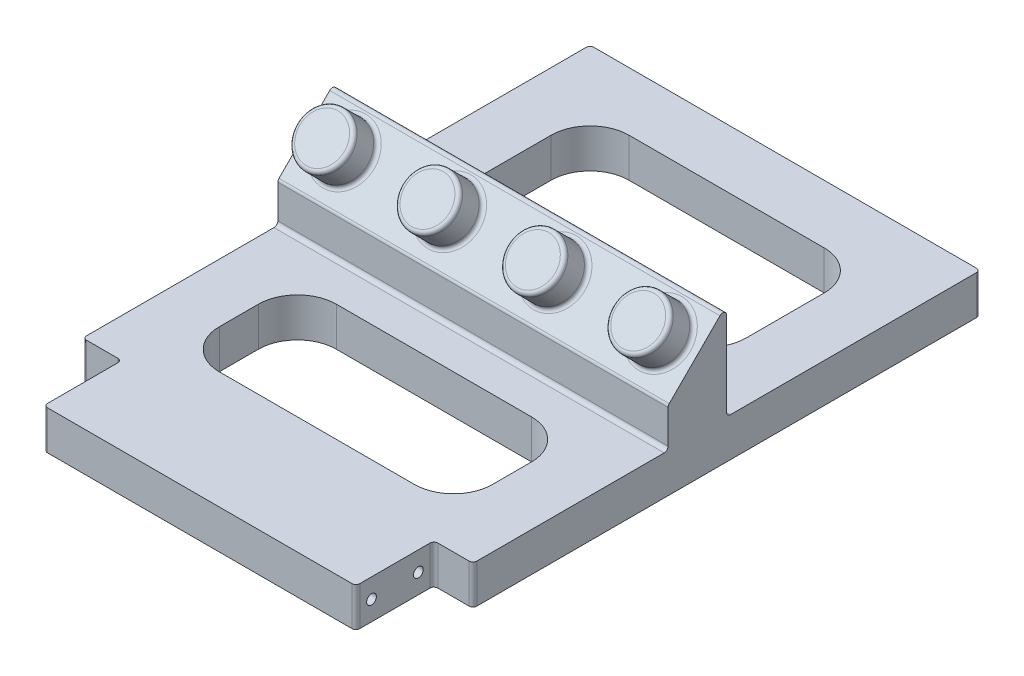
SolidWorks part; units mm, degrees
ref_plane "前视基准面" through (0, 0, 0) normal (0, 0, 1) x (1, 0, 0)
ref_plane "上视基准面" through (0, 0, 0) normal (0, 1, 0) x (1, 0, 0)
ref_plane "右视基准面" through (0, 0, 0) normal (1, 0, 0) x (0, 0, -1)
sketch "草图1" plane through (0, 0, 0) normal (0, 1, 0) x (1, 0, 0)
  line L1 (-50, -75) -> (50, -75)
  line L2 (-50, -75) -> (-50, 75)
  line L3 (-50, 75) -> (50, 75)
  line L4 (50, -75) -> (50, 75)
  line L5 (-50, -75) -> (50, 75) construction
  line L6 (-50, 75) -> (50, -75) construction
  point P0 (0, 0)
  dimension "D1" = 100
  dimension "D2" = 150
extrude "凸台-拉伸1" add sketch "草图1" along normal mid plane 10
sketch "草图6" plane through (50, 0, 0) normal (1, 0, 0) x (0, 0, -1)
  line L0 (-75, -5) -> (75, -5) construction
  line L1 (-55, -5) -> (-75, -5)
  line L2 (-55, -5) -> (-55, 5)
  line L3 (-55, 5) -> (-75, 5)
  line L4 (-75, -5) -> (-75, 5)
  line L5 (-55, -5) -> (-75, 5) construction
  line L6 (-55, 5) -> (-75, -5) construction
  point P0 (-65, 0)
  dimension "D1" = 20
extrude "切除-拉伸2" cut sketch "草图6" against normal blind 10
sketch "草图8" plane through (40, 0, 0) normal (1, 0, 0) x (0, 0, -1)
  line L0 (-55, -5) -> (-55, 5) construction
  line L1 (-55, -5) -> (-75, -5) construction
  line L2 (-55, -5) -> (-55, 5) construction
  line L3 (-55, 5) -> (-75, 5) construction
  line L4 (-75, -5) -> (-75, 5) construction
  line L5 (-55, -5) -> (-75, 5) construction
  line L6 (-55, 5) -> (-75, -5) construction
  line L7 (-55, -5) -> (-55, 5) construction
  line L8 (-55, -5) -> (75, -5) construction
  line L9 (-59, 0) -> (-71, 0) construction
  circle A0 centre (-71, 0) radius 1.25
  circle A1 centre (-59, 0) radius 1.25
  point P0 (-65, 0)
  point P19 (-65, 0)
  dimension "D2" = 2.5
  dimension "D1" = 12
extrude "切除-拉伸3" cut sketch "草图8" against normal blind 15
mirror "镜向1" about plane through (0, 0, 0) normal (1, 0, 0) of "切除-拉伸2", "切除-拉伸3"
sketch "草图9" plane through (50, 0, 0) normal (1, 0, 0) x (0, 0, -1)
  line L0 (-55, 5) -> (75, 5) construction
  line L1 (-5, 15) -> (10, 15) construction
  line L2 (-5, 15) -> (-5, 5)
  line L3 (-5, 5) -> (10, 5)
  line L4 (10, 15) -> (10, 5)
  line L5 (-5, 15) -> (10, 5) construction
  line L6 (-5, 5) -> (10, 15) construction
  line L7 (-5, 15) -> (10, 30)
  line L8 (10, 30) -> (10, 15)
  line L9 (-75, 5) -> (-75, -5) construction
  point P0 (2.5, 10)
  dimension "D1" = 45
  dimension "D2" = 15
  dimension "D3" = 10
  dimension "D4" = 70
extrude "凸台-拉伸3" add sketch "草图9" against normal up to surface (100 mm away) up to face at (-50, 0, -10)
sketch "草图10" plane through (0, 10, 10) normal (0, 0.7071, 0.7071) x (1, 0, 0)
  line L0 (-40.5, 17.6777) -> (40.5, 17.6777) construction
  line L2 (-50, 28.2843) -> (50, 7.0711) construction
  circle A0 centre (40.5, 17.6777) radius 6.75
  circle A1 centre (-40.5, 17.6777) radius 6.75
  circle A2 centre (-13.5, 17.6777) radius 6.75
  circle A3 centre (13.5, 17.6777) radius 6.75
  point P3 (0, 17.6777)
  dimension "D1" = 13.5
  dimension "D2" = 81
  dimension "D3" = 27
  dimension "D4" = 27
extrude "凸台-拉伸4" add sketch "草图10" along normal blind 8
fillet "圆角1" radius 1 12 edges at (-40.5, 17.727, 2.273) (-40.5, 23.3839, 7.9298) (-13.5, 17.727, 2.273) (-13.5, 23.3839, 7.9298) (13.5, 17.727, 2.273) (13.5, 23.3839, 7.9298) (40.5, 17.727, 2.273) (40.5, 23.3839, 7.9298) (0, 5, 5) (0, 5, -10) (0, 15, 5) (0, 30, -10)
fillet "圆角2" radius 1 8 edges at (50, 0, -75) (-50, 0, -75) (50, 0, 55) (40, 0, 55) (40, 0, 75) (-40, 0, 75) (-40, 0, 55) (-50, 0, 55)
sketch "草图11" plane through (0, 5, 0) normal (0, 1, 0) x (1, 0, 0)
  line L0 (49, 75) -> (-49, 75) construction
  line L1 (-35, 20) -> (35, 20)
  line L2 (-35, 20) -> (-35, 60)
  line L3 (-35, 60) -> (35, 60)
  line L4 (35, 20) -> (35, 60)
  line L5 (-35, 20) -> (35, 60) construction
  line L6 (-35, 60) -> (35, 20) construction
  line L7 (-35, -15) -> (35, -15)
  line L8 (-35, -15) -> (-35, -45)
  line L9 (-35, -45) -> (35, -45)
  line L10 (35, -15) -> (35, -45)
  line L11 (-35, -15) -> (35, -45) construction
  line L12 (-35, -45) -> (35, -15) construction
  line L13 (-41, -55) -> (-49, -55) construction
  point P0 (0, 40)
  point P5 (0, -30)
  dimension "D1" = 15
  dimension "D2" = 40
  dimension "D3" = 70
  dimension "D4" = 10
  dimension "D5" = 30
extrude "切除-拉伸4" cut sketch "草图11" against normal through all
fillet "圆角3" radius 10 8 edges at (-35, 0, 15) (35, 0, 15) (-35, 0, 45) (35, 0, 45) (35, 0, -20) (-35, 0, -20) (35, 0, -60) (-35, 0, -60)
